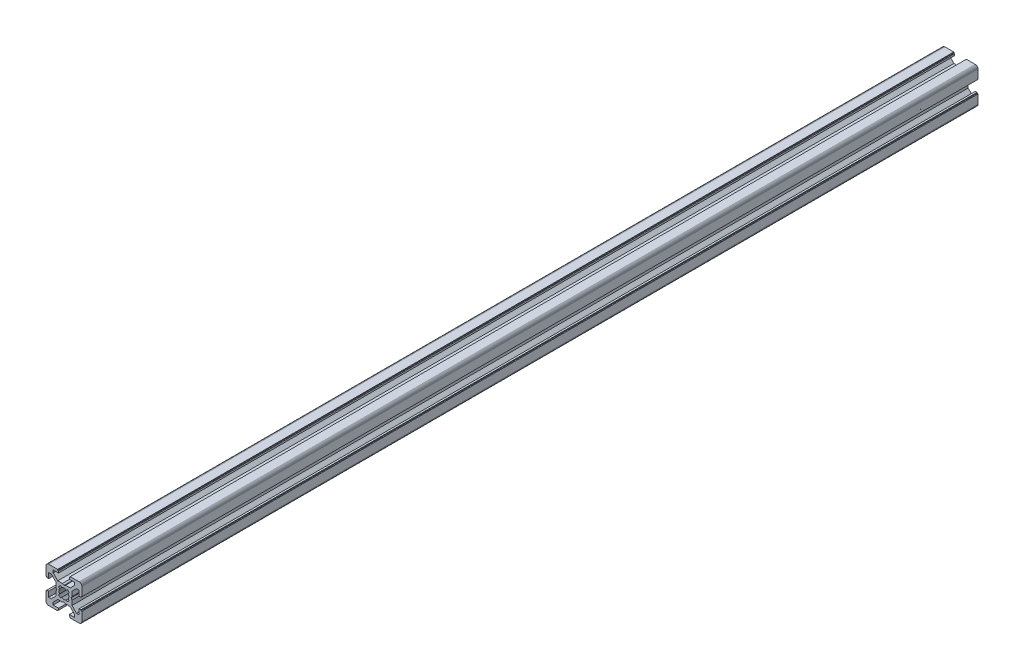
SolidWorks part; units mm, degrees
ref_plane "Front Plane" through (0, 0, 0) normal (0, 0, 1) x (1, 0, 0)
ref_plane "Top Plane" through (0, 0, 0) normal (0, 1, 0) x (1, 0, 0)
ref_plane "Right Plane" through (0, 0, 0) normal (1, 0, 0) x (0, 0, -1)
sketch "Sketch1" plane through (0, 0, 0) normal (0, 0, 1) x (1, 0, 0)
  line L0 (-70.0401, 44.0727) -> (-70.0416, 44.14)
  line L1 (-50.0416, 61.14) -> (-50.0431, 61.2073)
  line L2 (-62.7836, 52.4305) -> (-62.7907, 52.5701)
  line L3 (-57.2925, 52.7098) -> (-57.2996, 52.8494)
  line L4 (-70.0356, 44.0055) -> (-70.0401, 44.0727)
  line L5 (-50.0431, 61.2073) -> (-50.0476, 61.2744)
  line L6 (-62.7694, 52.2915) -> (-62.7836, 52.4305)
  line L7 (-57.2996, 52.8494) -> (-57.3138, 52.9884)
  line L8 (-70.028, 43.9386) -> (-70.0356, 44.0055)
  line L9 (-50.0476, 61.2744) -> (-50.0552, 61.3413)
  line L10 (-62.7482, 52.1534) -> (-62.7694, 52.2915)
  line L11 (-57.3138, 52.9884) -> (-57.335, 53.1266)
  line L12 (-70.0175, 43.8721) -> (-70.028, 43.9386)
  line L13 (-50.0552, 61.3413) -> (-50.0657, 61.4078)
  line L14 (-70.004, 43.8062) -> (-70.0175, 43.8721)
  line L15 (-50.0657, 61.4078) -> (-50.0792, 61.4738)
  line L16 (-62.72, 52.0165) -> (-62.7482, 52.1534)
  line L17 (-57.335, 53.1266) -> (-57.3632, 53.2634)
  line L18 (-69.9876, 43.7409) -> (-70.004, 43.8062)
  line L19 (-50.0792, 61.4738) -> (-50.0957, 61.539)
  line L20 (-62.6849, 51.8813) -> (-62.72, 52.0165)
  line L21 (-57.3632, 53.2634) -> (-57.3983, 53.3987)
  line L22 (-69.9682, 43.6765) -> (-69.9876, 43.7409)
  line L23 (-50.0957, 61.539) -> (-50.115, 61.6035)
  line L24 (-62.6429, 51.748) -> (-62.6849, 51.8813)
  line L25 (-57.3983, 53.3987) -> (-57.4403, 53.532)
  line L26 (-69.946, 43.6129) -> (-69.9682, 43.6765)
  line L27 (-50.115, 61.6035) -> (-50.1373, 61.667)
  line L28 (-62.5943, 51.617) -> (-62.6429, 51.748)
  line L29 (-57.4403, 53.532) -> (-57.489, 53.663)
  line L30 (-69.9209, 43.5504) -> (-69.946, 43.6129)
  line L31 (-50.1373, 61.667) -> (-50.1623, 61.7295)
  line L32 (-62.539, 51.4886) -> (-62.5943, 51.617)
  line L33 (-57.489, 53.663) -> (-57.5442, 53.7913)
  line L34 (-69.8931, 43.4892) -> (-69.9209, 43.5504)
  line L35 (-50.1623, 61.7295) -> (-50.1902, 61.7908)
  line L36 (-62.4773, 51.3633) -> (-62.539, 51.4886)
  line L37 (-57.5442, 53.7913) -> (-57.6059, 53.9167)
  line L38 (-69.8625, 43.4292) -> (-69.8931, 43.4892)
  line L39 (-50.1902, 61.7908) -> (-50.2207, 61.8508)
  line L40 (-69.8293, 43.3706) -> (-69.8625, 43.4292)
  line L41 (-50.2207, 61.8508) -> (-50.2539, 61.9093)
  line L42 (-55.5416, 51.774) -> (-56.0416, 52.64)
  line L43 (-64.0416, 52.64) -> (-64.5416, 53.506)
  line L44 (-69.7935, 43.3136) -> (-69.8293, 43.3706)
  line L45 (-50.2539, 61.9093) -> (-50.2897, 61.9663)
  line L46 (-62.913, 50.6387) -> (-62.9894, 50.753)
  line L47 (-57.0939, 54.527) -> (-57.1702, 54.6412)
  line L48 (-69.7551, 43.2583) -> (-69.7935, 43.3136)
  line L49 (-50.2897, 61.9663) -> (-50.3281, 62.0217)
  line L50 (-62.8322, 50.5276) -> (-62.913, 50.6387)
  line L51 (-57.1702, 54.6412) -> (-57.251, 54.7524)
  line L52 (-69.7144, 43.2047) -> (-69.7551, 43.2583)
  line L53 (-50.3281, 62.0217) -> (-50.3689, 62.0752)
  line L54 (-62.7472, 50.4196) -> (-62.8322, 50.5276)
  line L55 (-57.251, 54.7524) -> (-57.336, 54.8603)
  line L56 (-69.6712, 43.1531) -> (-69.7144, 43.2047)
  line L57 (-50.3689, 62.0752) -> (-50.412, 62.1269)
  line L58 (-57.0939, 50.753) -> (-57.6059, 51.3633)
  line L59 (-62.4773, 53.9167) -> (-62.9894, 54.527)
  line L60 (-62.6579, 50.3151) -> (-62.7472, 50.4196)
  line L61 (-57.336, 54.8603) -> (-57.4253, 54.9648)
  line L62 (-69.6258, 43.1034) -> (-69.6712, 43.1531)
  line L63 (-50.412, 62.1269) -> (-50.4574, 62.1766)
  line L64 (-62.5646, 50.2142) -> (-62.6579, 50.3151)
  line L65 (-57.4253, 54.9648) -> (-57.5186, 55.0657)
  line L66 (-62.4675, 50.117) -> (-62.5646, 50.2142)
  line L67 (-57.5186, 55.0657) -> (-57.6157, 55.1629)
  line L68 (-69.5782, 43.0558) -> (-69.6258, 43.1034)
  line L69 (-52.9809, 46.64) -> (-55.5416, 49.2006)
  line L70 (-64.5416, 56.0793) -> (-67.1023, 58.64)
  line L71 (-54.0416, 45.5793) -> (-56.6023, 48.14)
  line L72 (-63.4809, 57.14) -> (-66.0416, 59.7006)
  line L73 (-50.4574, 62.1766) -> (-50.505, 62.2242)
  line L74 (-62.3666, 50.0238) -> (-62.4675, 50.117)
  line L75 (-57.6157, 55.1629) -> (-57.7166, 55.2562)
  line L76 (-69.5285, 43.0104) -> (-69.5782, 43.0558)
  line L77 (-50.505, 62.2242) -> (-50.5547, 62.2696)
  line L78 (-62.2621, 49.9345) -> (-62.3666, 50.0238)
  line L79 (-57.7166, 55.2562) -> (-57.8211, 55.3454)
  line L80 (-58.1545, 49.6923) -> (-58.7648, 50.2044)
  line L81 (-61.3185, 55.0756) -> (-61.9287, 55.5877)
  line L82 (-69.4768, 42.9672) -> (-69.5285, 43.0104)
  line L83 (-50.5547, 62.2696) -> (-50.6064, 62.3127)
  line L84 (-62.1542, 49.8494) -> (-62.2621, 49.9345)
  line L85 (-57.8211, 55.3454) -> (-57.9291, 55.4305)
  line L86 (-69.4233, 42.9265) -> (-69.4768, 42.9672)
  line L87 (-50.6064, 62.3127) -> (-50.6599, 62.3535)
  line L88 (-62.043, 49.7687) -> (-62.1542, 49.8494)
  line L89 (-57.9291, 55.4305) -> (-58.0402, 55.5113)
  line L90 (-69.368, 42.8881) -> (-69.4233, 42.9265)
  line L91 (-50.6599, 62.3535) -> (-50.7153, 62.3918)
  line L92 (-61.9287, 49.6923) -> (-62.043, 49.7687)
  line L93 (-58.0402, 55.5113) -> (-58.1545, 55.5877)
  line L94 (-69.311, 42.8523) -> (-69.368, 42.8881)
  line L95 (-50.7153, 62.3918) -> (-50.7723, 62.4277)
  line L96 (-59.1756, 48.14) -> (-60.0416, 48.64)
  line L97 (-60.0416, 56.64) -> (-60.9076, 57.14)
  line L98 (-69.2524, 42.8191) -> (-69.311, 42.8523)
  line L99 (-50.7723, 62.4277) -> (-50.8308, 62.4609)
  line L100 (-69.1924, 42.7885) -> (-69.2524, 42.8191)
  line L101 (-50.8308, 62.4609) -> (-50.8908, 62.4914)
  line L102 (-61.1931, 50.1427) -> (-61.3185, 50.2044)
  line L103 (-58.7648, 55.0756) -> (-58.8901, 55.1373)
  line L104 (-69.1311, 42.7607) -> (-69.1924, 42.7885)
  line L105 (-50.8908, 62.4914) -> (-50.9521, 62.5193)
  line L106 (-61.0647, 50.0874) -> (-61.1931, 50.1427)
  line L107 (-58.8901, 55.1373) -> (-59.0185, 55.1926)
  line L108 (-69.0687, 42.7356) -> (-69.1311, 42.7607)
  line L109 (-50.9521, 62.5193) -> (-51.0145, 62.5443)
  line L110 (-60.9337, 50.0387) -> (-61.0647, 50.0874)
  line L111 (-59.0185, 55.1926) -> (-59.1495, 55.2413)
  line L112 (-69.0051, 42.7134) -> (-69.0687, 42.7356)
  line L113 (-51.0145, 62.5443) -> (-51.0781, 62.5666)
  line L114 (-60.8004, 49.9967) -> (-60.9337, 50.0387)
  line L115 (-59.1495, 55.2413) -> (-59.2828, 55.2832)
  line L116 (-68.9407, 42.694) -> (-69.0051, 42.7134)
  line L117 (-51.0781, 62.5666) -> (-51.1426, 62.5859)
  line L118 (-60.6651, 49.9616) -> (-60.8004, 49.9967)
  line L119 (-59.2828, 55.2832) -> (-59.4181, 55.3184)
  line L120 (-68.8754, 42.6776) -> (-68.9407, 42.694)
  line L121 (-51.1426, 62.5859) -> (-51.2078, 62.6024)
  line L122 (-60.5282, 49.9334) -> (-60.6651, 49.9616)
  line L123 (-59.4181, 55.3184) -> (-59.555, 55.3466)
  line L124 (-68.8094, 42.6641) -> (-68.8754, 42.6776)
  line L125 (-51.2078, 62.6024) -> (-51.2738, 62.6159)
  line L126 (-68.743, 42.6536) -> (-68.8094, 42.6641)
  line L127 (-51.2738, 62.6159) -> (-51.3403, 62.6264)
  line L128 (-60.3901, 49.9121) -> (-60.5282, 49.9334)
  line L129 (-59.555, 55.3466) -> (-59.6931, 55.3678)
  line L130 (-68.6761, 42.646) -> (-68.743, 42.6536)
  line L131 (-51.3403, 62.6264) -> (-51.4071, 62.6339)
  line L132 (-60.2511, 49.898) -> (-60.3901, 49.9121)
  line L133 (-59.6931, 55.3678) -> (-59.8321, 55.382)
  line L134 (-68.6089, 42.6415) -> (-68.6761, 42.646)
  line L135 (-51.4071, 62.6339) -> (-51.4743, 62.6385)
  line L136 (-60.1115, 49.8909) -> (-60.2511, 49.898)
  line L137 (-59.8321, 55.382) -> (-59.9717, 55.3891)
  line L138 (-68.5416, 42.64) -> (-68.6089, 42.6415)
  line L139 (-51.4743, 62.6385) -> (-51.5416, 62.64)
  line L140 (-68.5416, 42.64) -> (-63.5416, 42.64)
  line L141 (-56.5416, 42.64) -> (-51.5416, 42.64)
  line L142 (-63.5416, 43.14) -> (-63.0416, 43.14)
  line L143 (-57.0416, 43.14) -> (-56.5416, 43.14)
  line L144 (-66.0416, 44.14) -> (-63.0416, 44.14)
  line L145 (-57.0416, 44.14) -> (-54.0416, 44.14)
  line L146 (-68.5416, 46.64) -> (-67.1023, 46.64)
  line L147 (-52.9809, 46.64) -> (-51.5416, 46.64)
  line L148 (-63.4809, 48.14) -> (-60.9076, 48.14)
  line L149 (-59.1756, 48.14) -> (-56.6023, 48.14)
  line L150 (-70.0416, 49.14) -> (-69.5416, 49.14)
  line L151 (-50.5416, 49.14) -> (-50.0416, 49.14)
  line L152 (-69.5416, 49.64) -> (-68.5416, 49.64)
  line L153 (-51.5416, 49.64) -> (-50.5416, 49.64)
  line L154 (-60.1115, 49.8909) -> (-59.9717, 49.8909)
  line L155 (-60.1115, 55.3891) -> (-59.9717, 55.3891)
  line L156 (-51.5416, 55.64) -> (-50.5416, 55.64)
  line L157 (-69.5416, 55.64) -> (-68.5416, 55.64)
  line L158 (-50.5416, 56.14) -> (-50.0416, 56.14)
  line L159 (-70.0416, 56.14) -> (-69.5416, 56.14)
  line L160 (-59.1756, 57.14) -> (-56.6023, 57.14)
  line L161 (-63.4809, 57.14) -> (-60.9076, 57.14)
  line L162 (-52.9809, 58.64) -> (-51.5416, 58.64)
  line L163 (-68.5416, 58.64) -> (-67.1023, 58.64)
  line L164 (-57.0416, 61.14) -> (-54.0416, 61.14)
  line L165 (-66.0416, 61.14) -> (-63.0416, 61.14)
  line L166 (-57.0416, 62.14) -> (-56.5416, 62.14)
  line L167 (-63.5416, 62.14) -> (-63.0416, 62.14)
  line L168 (-56.5416, 62.64) -> (-51.5416, 62.64)
  line L169 (-68.5416, 62.64) -> (-63.5416, 62.64)
  line L170 (-51.5416, 42.64) -> (-51.4743, 42.6415)
  line L171 (-68.6089, 62.6385) -> (-68.5416, 62.64)
  line L172 (-59.9717, 49.8909) -> (-59.8321, 49.898)
  line L173 (-60.2511, 55.382) -> (-60.1115, 55.3891)
  line L174 (-51.4743, 42.6415) -> (-51.4071, 42.646)
  line L175 (-68.6761, 62.6339) -> (-68.6089, 62.6385)
  line L176 (-59.8321, 49.898) -> (-59.6931, 49.9121)
  line L177 (-60.3901, 55.3678) -> (-60.2511, 55.382)
  line L178 (-51.4071, 42.646) -> (-51.3403, 42.6536)
  line L179 (-68.743, 62.6264) -> (-68.6761, 62.6339)
  line L180 (-59.6931, 49.9121) -> (-59.555, 49.9334)
  line L181 (-60.5282, 55.3466) -> (-60.3901, 55.3678)
  line L182 (-51.3403, 42.6536) -> (-51.2738, 42.6641)
  line L183 (-68.8094, 62.6159) -> (-68.743, 62.6264)
  line L184 (-51.2738, 42.6641) -> (-51.2078, 42.6776)
  line L185 (-68.8754, 62.6024) -> (-68.8094, 62.6159)
  line L186 (-59.555, 49.9334) -> (-59.4181, 49.9616)
  line L187 (-60.6651, 55.3184) -> (-60.5282, 55.3466)
  line L188 (-51.2078, 42.6776) -> (-51.1426, 42.694)
  line L189 (-68.9407, 62.5859) -> (-68.8754, 62.6024)
  line L190 (-59.4181, 49.9616) -> (-59.2828, 49.9967)
  line L191 (-60.8004, 55.2832) -> (-60.6651, 55.3184)
  line L192 (-51.1426, 42.694) -> (-51.0781, 42.7134)
  line L193 (-69.0051, 62.5666) -> (-68.9407, 62.5859)
  line L194 (-59.2828, 49.9967) -> (-59.1495, 50.0387)
  line L195 (-60.9337, 55.2413) -> (-60.8004, 55.2832)
  line L196 (-51.0781, 42.7134) -> (-51.0145, 42.7356)
  line L197 (-69.0687, 62.5443) -> (-69.0051, 62.5666)
  line L198 (-59.1495, 50.0387) -> (-59.0185, 50.0874)
  line L199 (-61.0647, 55.1926) -> (-60.9337, 55.2413)
  line L200 (-51.0145, 42.7356) -> (-50.9521, 42.7607)
  line L201 (-69.1311, 62.5193) -> (-69.0687, 62.5443)
  line L202 (-59.0185, 50.0874) -> (-58.8901, 50.1427)
  line L203 (-61.1931, 55.1373) -> (-61.0647, 55.1926)
  line L204 (-50.9521, 42.7607) -> (-50.8908, 42.7885)
  line L205 (-69.1924, 62.4914) -> (-69.1311, 62.5193)
  line L206 (-58.8901, 50.1427) -> (-58.7648, 50.2044)
  line L207 (-61.3185, 55.0756) -> (-61.1931, 55.1373)
  line L208 (-50.8908, 42.7885) -> (-50.8308, 42.8191)
  line L209 (-69.2524, 62.4609) -> (-69.1924, 62.4914)
  line L210 (-50.8308, 42.8191) -> (-50.7723, 42.8523)
  line L211 (-69.311, 62.4277) -> (-69.2524, 62.4609)
  line L212 (-60.9076, 48.14) -> (-60.0416, 48.64)
  line L213 (-60.0416, 56.64) -> (-59.1756, 57.14)
  line L214 (-50.7723, 42.8523) -> (-50.7153, 42.8881)
  line L215 (-69.368, 62.3918) -> (-69.311, 62.4277)
  line L216 (-58.1545, 49.6923) -> (-58.0402, 49.7687)
  line L217 (-62.043, 55.5113) -> (-61.9287, 55.5877)
  line L218 (-50.7153, 42.8881) -> (-50.6599, 42.9265)
  line L219 (-69.4233, 62.3535) -> (-69.368, 62.3918)
  line L220 (-58.0402, 49.7687) -> (-57.9291, 49.8494)
  line L221 (-62.1542, 55.4305) -> (-62.043, 55.5113)
  line L222 (-50.6599, 42.9265) -> (-50.6064, 42.9672)
  line L223 (-69.4768, 62.3127) -> (-69.4233, 62.3535)
  line L224 (-57.9291, 49.8494) -> (-57.8211, 49.9345)
  line L225 (-62.2621, 55.3454) -> (-62.1542, 55.4305)
  line L226 (-50.6064, 42.9672) -> (-50.5547, 43.0104)
  line L227 (-69.5285, 62.2696) -> (-69.4768, 62.3127)
  line L228 (-61.9287, 49.6923) -> (-61.3185, 50.2044)
  line L229 (-58.7648, 55.0756) -> (-58.1545, 55.5877)
  line L230 (-57.8211, 49.9345) -> (-57.7166, 50.0238)
  line L231 (-62.3666, 55.2562) -> (-62.2621, 55.3454)
  line L232 (-50.5547, 43.0104) -> (-50.505, 43.0558)
  line L233 (-69.5782, 62.2242) -> (-69.5285, 62.2696)
  line L234 (-57.7166, 50.0238) -> (-57.6157, 50.117)
  line L235 (-62.4675, 55.1629) -> (-62.3666, 55.2562)
  line L236 (-50.505, 43.0558) -> (-50.4574, 43.1034)
  line L237 (-67.1023, 46.64) -> (-64.5416, 49.2006)
  line L238 (-55.5416, 56.0793) -> (-52.9809, 58.64)
  line L239 (-66.0416, 45.5793) -> (-63.4809, 48.14)
  line L240 (-56.6023, 57.14) -> (-54.0416, 59.7006)
  line L241 (-69.6258, 62.1766) -> (-69.5782, 62.2242)
  line L242 (-57.6157, 50.117) -> (-57.5186, 50.2142)
  line L243 (-62.5646, 55.0657) -> (-62.4675, 55.1629)
  line L244 (-57.5186, 50.2142) -> (-57.4253, 50.3151)
  line L245 (-62.6579, 54.9648) -> (-62.5646, 55.0657)
  line L246 (-50.4574, 43.1034) -> (-50.412, 43.1531)
  line L247 (-69.6712, 62.1269) -> (-69.6258, 62.1766)
  line L248 (-57.4253, 50.3151) -> (-57.336, 50.4196)
  line L249 (-62.7472, 54.8603) -> (-62.6579, 54.9648)
  line L250 (-62.9894, 50.753) -> (-62.4773, 51.3633)
  line L251 (-57.6059, 53.9167) -> (-57.0939, 54.527)
  line L252 (-50.412, 43.1531) -> (-50.3689, 43.2047)
  line L253 (-69.7144, 62.0752) -> (-69.6712, 62.1269)
  line L254 (-57.336, 50.4196) -> (-57.251, 50.5276)
  line L255 (-62.8322, 54.7524) -> (-62.7472, 54.8603)
  line L256 (-50.3689, 43.2047) -> (-50.3281, 43.2583)
  line L257 (-69.7551, 62.0217) -> (-69.7144, 62.0752)
  line L258 (-57.251, 50.5276) -> (-57.1702, 50.6387)
  line L259 (-62.913, 54.6412) -> (-62.8322, 54.7524)
  line L260 (-50.3281, 43.2583) -> (-50.2897, 43.3136)
  line L261 (-69.7935, 61.9663) -> (-69.7551, 62.0217)
  line L262 (-57.1702, 50.6387) -> (-57.0939, 50.753)
  line L263 (-62.9894, 54.527) -> (-62.913, 54.6412)
  line L264 (-50.2897, 43.3136) -> (-50.2539, 43.3706)
  line L265 (-69.8293, 61.9093) -> (-69.7935, 61.9663)
  line L266 (-64.5416, 51.774) -> (-64.0416, 52.64)
  line L267 (-56.0416, 52.64) -> (-55.5416, 53.506)
  line L268 (-50.2539, 43.3706) -> (-50.2207, 43.4292)
  line L269 (-69.8625, 61.8508) -> (-69.8293, 61.9093)
  line L270 (-50.2207, 43.4292) -> (-50.1902, 43.4892)
  line L271 (-69.8931, 61.7908) -> (-69.8625, 61.8508)
  line L272 (-57.6059, 51.3633) -> (-57.5442, 51.4886)
  line L273 (-62.539, 53.7913) -> (-62.4773, 53.9167)
  line L274 (-50.1902, 43.4892) -> (-50.1623, 43.5504)
  line L275 (-69.9209, 61.7295) -> (-69.8931, 61.7908)
  line L276 (-57.5442, 51.4886) -> (-57.489, 51.617)
  line L277 (-62.5943, 53.663) -> (-62.539, 53.7913)
  line L278 (-50.1623, 43.5504) -> (-50.1373, 43.6129)
  line L279 (-69.946, 61.667) -> (-69.9209, 61.7295)
  line L280 (-57.489, 51.617) -> (-57.4403, 51.748)
  line L281 (-62.6429, 53.532) -> (-62.5943, 53.663)
  line L282 (-50.1373, 43.6129) -> (-50.115, 43.6765)
  line L283 (-69.9682, 61.6035) -> (-69.946, 61.667)
  line L284 (-57.4403, 51.748) -> (-57.3983, 51.8813)
  line L285 (-62.6849, 53.3987) -> (-62.6429, 53.532)
  line L286 (-50.115, 43.6765) -> (-50.0957, 43.7409)
  line L287 (-69.9876, 61.539) -> (-69.9682, 61.6035)
  line L288 (-57.3983, 51.8813) -> (-57.3632, 52.0165)
  line L289 (-62.72, 53.2634) -> (-62.6849, 53.3987)
  line L290 (-50.0957, 43.7409) -> (-50.0792, 43.8062)
  line L291 (-70.004, 61.4738) -> (-69.9876, 61.539)
  line L292 (-57.3632, 52.0165) -> (-57.335, 52.1534)
  line L293 (-62.7482, 53.1266) -> (-62.72, 53.2634)
  line L294 (-50.0792, 43.8062) -> (-50.0657, 43.8721)
  line L295 (-70.0175, 61.4078) -> (-70.004, 61.4738)
  line L296 (-50.0657, 43.8721) -> (-50.0552, 43.9386)
  line L297 (-70.028, 61.3413) -> (-70.0175, 61.4078)
  line L298 (-57.335, 52.1534) -> (-57.3138, 52.2915)
  line L299 (-62.7694, 52.9884) -> (-62.7482, 53.1266)
  line L300 (-50.0552, 43.9386) -> (-50.0476, 44.0055)
  line L301 (-70.0356, 61.2744) -> (-70.028, 61.3413)
  line L302 (-57.3138, 52.2915) -> (-57.2996, 52.4305)
  line L303 (-62.7836, 52.8494) -> (-62.7694, 52.9884)
  line L304 (-50.0476, 44.0055) -> (-50.0431, 44.0727)
  line L305 (-70.0401, 61.2073) -> (-70.0356, 61.2744)
  line L306 (-57.2996, 52.4305) -> (-57.2925, 52.5701)
  line L307 (-62.7907, 52.7098) -> (-62.7836, 52.8494)
  line L308 (-50.0431, 44.0727) -> (-50.0416, 44.14)
  line L309 (-70.0416, 61.14) -> (-70.0401, 61.2073)
  line L310 (-70.0416, 56.14) -> (-70.0416, 61.14)
  line L311 (-70.0416, 44.14) -> (-70.0416, 49.14)
  line L312 (-69.5416, 55.64) -> (-69.5416, 56.14)
  line L313 (-69.5416, 49.14) -> (-69.5416, 49.64)
  line L314 (-68.5416, 55.64) -> (-68.5416, 58.64)
  line L315 (-68.5416, 46.64) -> (-68.5416, 49.64)
  line L316 (-66.0416, 59.7006) -> (-66.0416, 61.14)
  line L317 (-66.0416, 44.14) -> (-66.0416, 45.5793)
  line L318 (-64.5416, 53.506) -> (-64.5416, 56.0793)
  line L319 (-64.5416, 49.2006) -> (-64.5416, 51.774)
  line L320 (-63.5416, 62.14) -> (-63.5416, 62.64)
  line L321 (-63.5416, 42.64) -> (-63.5416, 43.14)
  line L322 (-63.0416, 61.14) -> (-63.0416, 62.14)
  line L323 (-63.0416, 43.14) -> (-63.0416, 44.14)
  line L324 (-62.7907, 52.5701) -> (-62.7907, 52.7098)
  line L325 (-57.2925, 52.5701) -> (-57.2925, 52.7098)
  line L326 (-57.0416, 61.14) -> (-57.0416, 62.14)
  line L327 (-57.0416, 43.14) -> (-57.0416, 44.14)
  line L328 (-56.5416, 62.14) -> (-56.5416, 62.64)
  line L329 (-56.5416, 42.64) -> (-56.5416, 43.14)
  line L330 (-55.5416, 49.2006) -> (-55.5416, 51.774)
  line L331 (-55.5416, 53.506) -> (-55.5416, 56.0793)
  line L332 (-54.0416, 59.7006) -> (-54.0416, 61.14)
  line L333 (-54.0416, 44.14) -> (-54.0416, 45.5793)
  line L334 (-51.5416, 55.64) -> (-51.5416, 58.64)
  line L335 (-51.5416, 46.64) -> (-51.5416, 49.64)
  line L336 (-50.5416, 55.64) -> (-50.5416, 56.14)
  line L337 (-50.5416, 49.14) -> (-50.5416, 49.64)
  line L338 (-50.0416, 56.14) -> (-50.0416, 61.14)
  line L339 (-50.0416, 44.14) -> (-50.0416, 49.14)
extrude "Boss-Extrude1" add sketch "Sketch1" along normal blind 500
